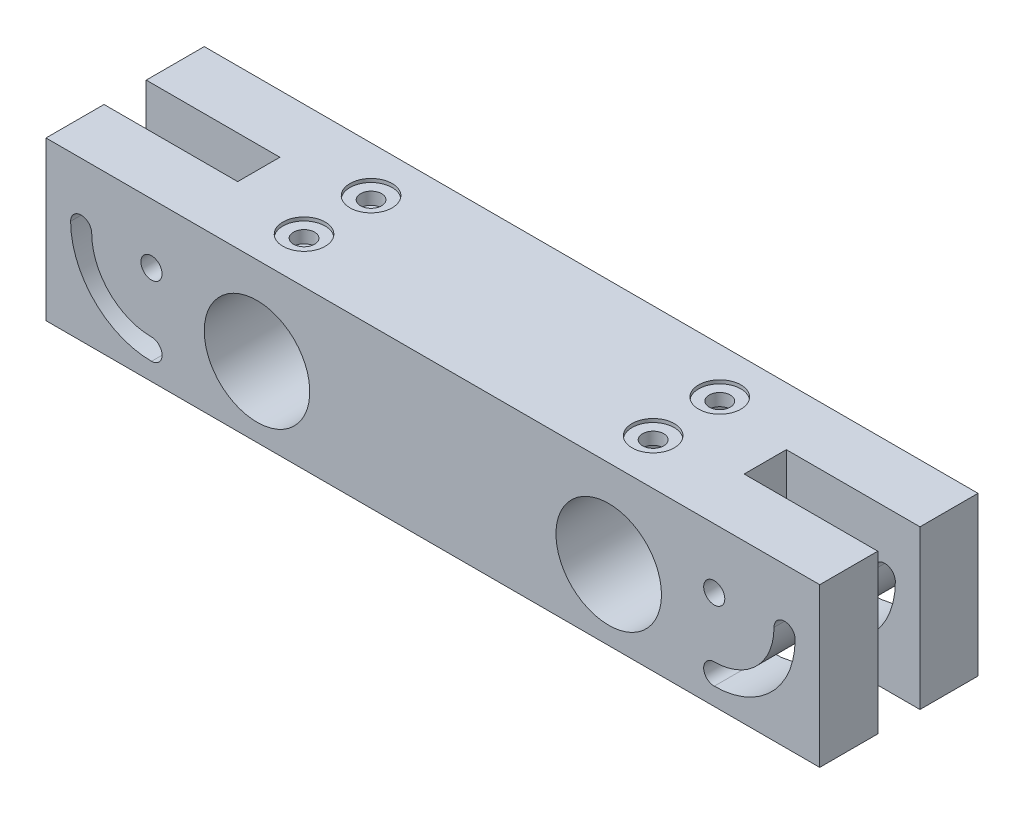
SolidWorks part; units mm, degrees
ref_plane "Front Plane" through (0, 0, 0) normal (0, 0, 1) x (1, 0, 0)
ref_plane "Top Plane" through (0, 0, 0) normal (0, 1, 0) x (1, 0, 0)
ref_plane "Right Plane" through (0, 0, 0) normal (1, 0, 0) x (0, 0, -1)
sketch "Sketch1" plane through (0, 0, 0) normal (0, 0, 1) x (1, 0, 0)
  line L1 (0, 0) -> (110, 0)
  line L2 (0, 0) -> (0, 45)
  line L3 (0, 45) -> (110, 45)
  line L4 (110, 0) -> (110, 45)
  circle A0 centre (50, 20) radius 15
  circle A1 centre (80, 28) radius 3
  arc A2 (80, 5) -> (103, 28) centre (80, 28) ccw
  arc A3 (80, 5) -> (80, 11) centre (80, 8) cw
  arc A4 (103, 28) -> (97, 28) centre (100, 28) ccw
  arc A5 (80, 11) -> (97, 28) centre (80, 28) ccw
  point P9 (80, 8)
  point P10 (100, 28)
  dimension "D3" = 30
  dimension "D4" = 60
  dimension "D5" = 6
  dimension "D1" = 110
  dimension "D2" = 45
  dimension "D6" = 25
  dimension "D7" = 8
  dimension "D8" = 20
  dimension "D9" = 20
  dimension "D10" = 30
  dimension "D11" = 3
  dimension "D12" = 3
  dimension "D13" = 10
  dimension "D14" = 30
extrude "Boss-Extrude1" add sketch "Sketch1" along normal blind 45
sketch "Sketch3" plane through (0, 45, 0) normal (0, 1, 0) x (1, 0, 0)
  line L3 (0, -45) -> (110, -45) construction
  line L4 (55.4854, -32) -> (52.5986, -27)
  line L5 (52.5986, -27) -> (46.8251, -27)
  line L6 (46.8251, -27) -> (43.9384, -32)
  line L7 (43.9384, -32) -> (46.8251, -37)
  line L8 (46.8251, -37) -> (52.5986, -37)
  line L9 (52.5986, -37) -> (55.4854, -32)
  line L10 (55.4854, -13) -> (52.5986, -8)
  line L11 (52.5986, -8) -> (46.8251, -8)
  line L12 (46.8251, -8) -> (43.9384, -13)
  line L13 (43.9384, -13) -> (46.8251, -18)
  line L14 (46.8251, -18) -> (52.5986, -18)
  line L15 (52.5986, -18) -> (55.4854, -13)
  line L16 (0, 0) -> (110, 0) construction
  circle A0 centre (49.7119, -32) radius 5 construction
  circle A1 centre (49.7119, -13) radius 5 construction
  dimension "D1" = 10
  dimension "D2" = 8
  dimension "D3" = 10
  dimension "D4" = 8
extrude "Cut-Extrude4" cut sketch "Sketch3" against normal up to next
sketch "Sketch9" plane through (0, 45, 0) normal (0, 1, 0) x (1, 0, 0)
  line L0 (46.8251, -8) -> (43.9384, -13)
  line L1 (43.9384, -13) -> (46.8251, -18)
  line L2 (46.8251, -18) -> (52.5986, -18)
  line L3 (52.5986, -18) -> (55.4854, -13)
  line L4 (55.4854, -13) -> (52.5986, -8)
  line L5 (52.5986, -8) -> (46.8251, -8)
extrude "Boss-Extrude2" add sketch "Sketch9" against normal blind 4.5
sketch "Sketch10" plane through (0, 45, 0) normal (0, 1, 0) x (1, 0, 0)
  line L0 (43.9384, -32) -> (46.8251, -37)
  line L1 (46.8251, -37) -> (52.5986, -37)
  line L2 (52.5986, -37) -> (55.4854, -32)
  line L3 (55.4854, -32) -> (52.5986, -27)
  line L4 (52.5986, -27) -> (46.8251, -27)
  line L5 (46.8251, -27) -> (43.9384, -32)
extrude "Boss-Extrude3" add sketch "Sketch10" against normal blind 4.5
sketch "Sketch12" plane through (0, 40.5, 0) normal (0, -1, 0) x (1, 0, 0)
  line L0 (52.5986, 8) -> (46.8251, 8) construction
  circle A0 centre (49.5765, 13) radius 3
  dimension "D2" = 6
  dimension "D1" = 5
extrude "Cut-Extrude5" cut sketch "Sketch12" against normal up to surface (4.5 mm away) contours A0 up to face at (55, 45, 22.5)
sketch "Sketch15" plane through (0, 40.5, 0) normal (0, -1, 0) x (1, 0, 0)
  line L0 (52.5986, 27) -> (46.8251, 27) construction
  circle A0 centre (49.6304, 32) radius 3
  dimension "D1" = 6
  dimension "D2" = 5
extrude "Cut-Extrude6" cut sketch "Sketch15" against normal up to surface (4.5 mm away) contours A0 up to face at (49.5765, 45, 16)
sketch "Sketch16" plane through (0, 45, 0) normal (0, 1, 0) x (1, 0, 0)
  circle A0 centre (49.6304, -32) radius 6
  circle A1 centre (49.5765, -13) radius 6
  dimension "D1" = 12
  dimension "D2" = 12
extrude "Cut-Extrude7" cut sketch "Sketch16" against normal blind 1
sketch "Sketch18" plane through (0, 45, 0) normal (0, 1, 0) x (1, 0, 0)
  line L0 (110, -45) -> (110, 0) construction
  line L1 (110, -16.5) -> (72, -16.5)
  line L2 (110, -16.5) -> (110, -28.5)
  line L3 (110, -28.5) -> (72, -28.5)
  line L4 (72, -16.5) -> (72, -28.5)
  line L5 (0, 0) -> (110, 0) construction
  dimension "D1" = 16.5
  dimension "D2" = 12
  dimension "D3" = 38
extrude "Cut-Extrude8" cut sketch "Sketch18" against normal through all
mirror "Mirror1" about plane through (0, 0, 45) normal (-1, 0, 0) of "Boss-Extrude1", "Cut-Extrude5", "Cut-Extrude6", "Cut-Extrude7", "Cut-Extrude8"
